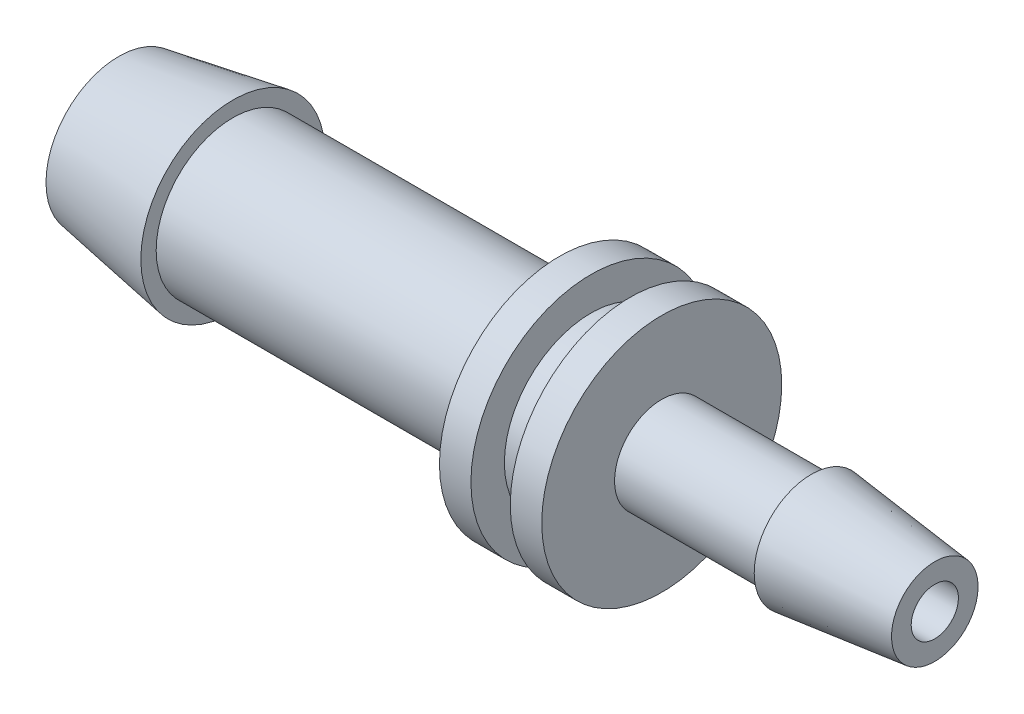
SolidWorks part; units mm, degrees
ref_plane "Front Plane" through (0, 0, 0) normal (0, 0, 1) x (1, 0, 0)
ref_plane "Top Plane" through (0, 0, 0) normal (0, 1, 0) x (1, 0, 0)
ref_plane "Right Plane" through (0, 0, 0) normal (1, 0, 0) x (0, 0, -1)
sketch "Sketch1" plane through (0, 0, 0) normal (0, 0, 1) x (1, 0, 0)
  line L0 (0, 0) -> (0.762, 0) construction
  line L1 (0, 2.3495) -> (3.683, 2.9718)
  line L2 (0, -55) -> (0, 55) construction
  line L3 (3.683, 2.9718) -> (3.683, 2.4765)
  line L4 (3.683, 2.4765) -> (14.224, 2.4765)
  line L5 (14.224, 2.4765) -> (14.224, 3.8735)
  line L6 (14.224, 3.8735) -> (15.24, 3.8735)
  line L7 (15.24, 3.8735) -> (15.24, 2.794)
  line L8 (15.24, 2.794) -> (16.51, 2.794)
  line L9 (16.51, 2.794) -> (16.51, 3.8735)
  line L10 (16.51, 3.8735) -> (17.526, 3.8735)
  line L11 (17.526, 3.8735) -> (17.526, 1.524)
  line L12 (17.526, 1.524) -> (22.352, 1.524)
  line L13 (22.352, 1.524) -> (22.352, 1.8415)
  line L14 (22.352, 1.8415) -> (26.3398, 1.397)
  line L15 (26.3398, 1.397) -> (26.3398, 0.762)
  line L16 (26.3398, 0.762) -> (0, 0.762)
  line L18 (0, 2.3495) -> (0, 0.762)
  line L19 (55, 0) -> (-55, 0) construction
  point P20 (0, 0)
  point P22 (0, 0)
  point P23 (0, 0)
  point P24 (0, 0)
  point P25 (0, 0)
  point P26 (0, 0)
  point P27 (0, 0)
  point P28 (0, 0)
  point P29 (0, 0)
  point P30 (0, 0)
  point P31 (0, 0)
  point P32 (0, 0)
  point P33 (37.8507, 0)
  dimension "D1" = 0.762
  dimension "D2" = 2.9718
  dimension "D3" = 2.3495
  dimension "D4" = 1.397
revolve "Revolve1" add sketch "Sketch1" angle 360 about L0
